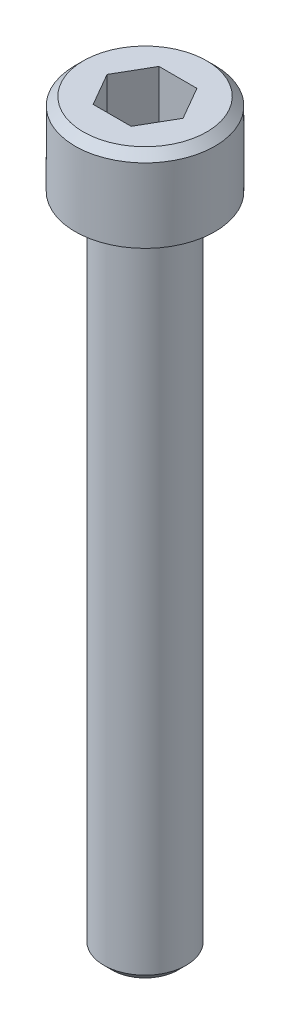
SolidWorks part; units mm, degrees
material "1023 Carbon Steel Sheet (SS)"
ref_plane "Front Plane" through (0, 0, 0) normal (0, 0, 1) x (1, 0, 0)
ref_plane "Top Plane" through (0, 0, 0) normal (0, 1, 0) x (1, 0, 0)
ref_plane "Right Plane" through (0, 0, 0) normal (1, 0, 0) x (0, 0, -1)
sketch "Sketch1" plane through (0, 0, 0) normal (0, 0, 1) x (1, 0, 0)
  line L0 (0, 0) -> (4.25, 0)
  line L1 (4.25, 0) -> (4.25, -5)
  line L2 (4.25, -5) -> (2.5, -5)
  line L3 (2.5, -5) -> (2.5, -45)
  line L4 (2.5, -45) -> (0, -45)
  line L5 (0, -45) -> (0, 0)
  dimension "D1" = 2.5
  dimension "D2" = 45
  dimension "D3" = 5
  dimension "D4" = 4.25
revolve "Revolve1" add sketch "Sketch1" angle 360 about L5
chamfer "Chamfer1" distance 0.5 angle 45 2 edges at (0, -45, -2.5) (0, 0, -4.25)
sketch "Sketch2" plane through (0, 0, 0) normal (0, 0, 1) x (1, 0, 0)
  line L0 (3.95, -4.9) -> (2.5, -4.9)
  line L1 (2.5, -4.9) -> (2.5, -5.6796)
  line L2 (2.5, -44.5) -> (2.5, -5) construction
  line L3 (2.5, -5.6796) -> (4.05, -5.6796)
  line L4 (3.95, -4.9) -> (4.05, -5)
  line L5 (4.05, -5) -> (4.05, -5.6796)
  line L6 (-4.25, -5) -> (4.25, -5) construction
  line L7 (0, 0) -> (0, -3.1564) construction
  dimension "D1" = 0.1
  dimension "D2" = 2.5
  dimension "D3" = 45
  dimension "D4" = 0.2
revolve "Cut-Revolve1" cut sketch "Sketch2" angle 360 about L7
fillet "Fillet2" radius 1 1 edges at (0, -4.9, 2.5)
sketch "Sketch3" plane through (0, 0, 0) normal (0, 1, 0) x (1, 0, 0)
  line L1 (-1.1547, 2) -> (-2.3094, 0)
  line L2 (-2.3094, 0) -> (-1.1547, -2)
  line L3 (-1.1547, -2) -> (1.1547, -2)
  line L4 (1.1547, -2) -> (2.3094, 0)
  line L5 (2.3094, 0) -> (1.1547, 2)
  line L6 (1.1547, 2) -> (-1.1547, 2)
  circle A0 centre (0, 0) radius 2 construction
  dimension "D1" = 4
extrude "Cut-Extrude1" cut sketch "Sketch3" against normal blind 4
equation "\"D4@Sketch1\"=8.5/2"
